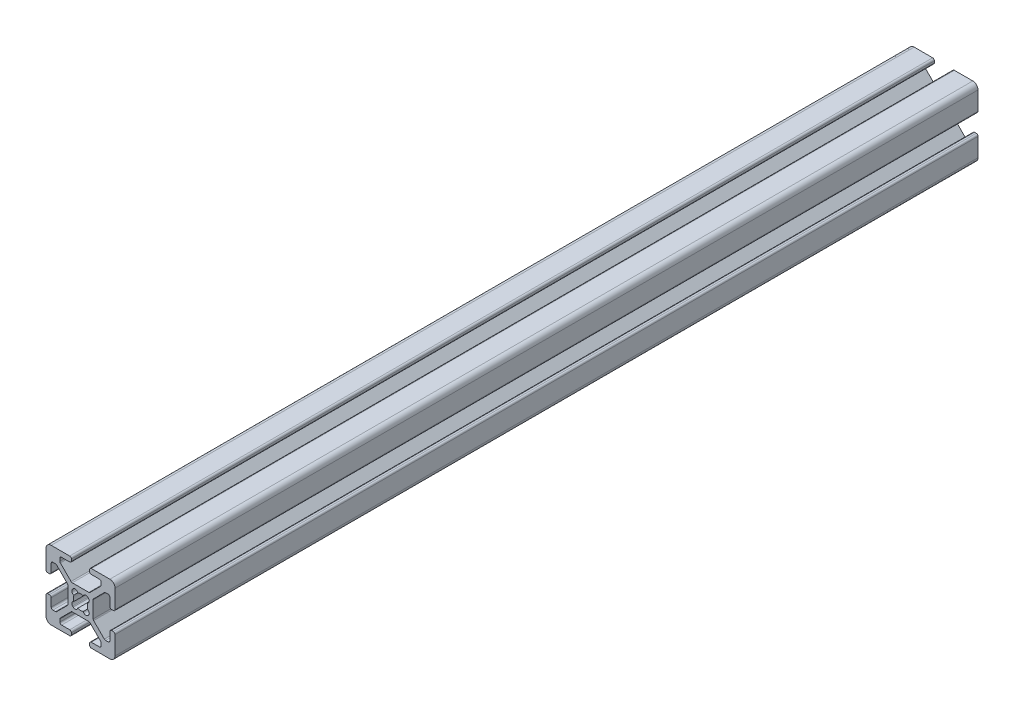
SolidWorks part; units mm, degrees
material "1060 Alloy"
ref_plane "Front Plane" through (0, 0, 0) normal (0, 0, 1) x (1, 0, 0)
ref_plane "Top Plane" through (0, 0, 0) normal (0, 1, 0) x (1, 0, 0)
ref_plane "Right Plane" through (0, 0, 0) normal (1, 0, 0) x (0, 0, -1)
sketch "Sketch2" plane through (0, 0, 0) normal (0, 0, 1) x (1, 0, 0)
  line L0 (-10, -3.138) -> (-10, -8.5)
  line L1 (-8.5, -10) -> (-3.138, -10)
  line L2 (-2.63, -9.492) -> (-2.63, -9.008)
  line L3 (-3.138, -8.5) -> (-5.487, -8.5)
  line L4 (-5.995, -7.992) -> (-5.995, -7.2662)
  line L5 (-5.8462, -6.907) -> (-2.743, -3.8038)
  line L6 (-2.3838, -3.655) -> (2.3841, -3.655)
  line L7 (2.7433, -3.8038) -> (5.8462, -6.9067)
  line L8 (5.995, -7.2659) -> (5.995, -7.992)
  line L9 (5.487, -8.5) -> (3.138, -8.5)
  line L10 (2.63, -9.008) -> (2.63, -9.492)
  line L11 (3.138, -10) -> (8.5, -10)
  line L12 (10, -8.5) -> (10, -3.138)
  line L13 (9.492, -2.63) -> (9.008, -2.63)
  line L14 (8.5, -3.138) -> (8.5, -5.487)
  line L15 (7.992, -5.995) -> (7.2662, -5.995)
  line L16 (6.907, -5.8462) -> (3.8038, -2.743)
  line L17 (3.655, -2.3838) -> (3.655, 2.3841)
  line L18 (3.8038, 2.7433) -> (6.9067, 5.8462)
  line L19 (7.2659, 5.995) -> (7.992, 5.995)
  line L20 (8.5, 5.487) -> (8.5, 3.138)
  line L21 (9.008, 2.63) -> (9.492, 2.63)
  line L22 (10, 3.138) -> (10, 8.5)
  line L23 (8.5, 10) -> (3.138, 10)
  line L24 (2.63, 9.492) -> (2.63, 9.008)
  line L25 (3.138, 8.5) -> (5.487, 8.5)
  line L26 (5.995, 7.992) -> (5.995, 7.2662)
  line L27 (5.8462, 6.907) -> (2.743, 3.8038)
  line L28 (2.3838, 3.655) -> (-2.3841, 3.655)
  line L29 (-2.7433, 3.8038) -> (-5.8462, 6.9067)
  line L30 (-5.995, 7.2659) -> (-5.995, 7.992)
  line L31 (-5.487, 8.5) -> (-3.138, 8.5)
  line L32 (-2.63, 9.008) -> (-2.63, 9.492)
  line L33 (-3.138, 10) -> (-8.5, 10)
  line L34 (-10, 8.5) -> (-10, 3.138)
  line L35 (-9.492, 2.63) -> (-9.008, 2.63)
  line L36 (-8.5, 3.138) -> (-8.5, 5.487)
  line L37 (-7.992, 5.995) -> (-7.2662, 5.995)
  line L38 (-6.907, 5.8462) -> (-3.8038, 2.743)
  line L39 (-3.655, 2.3838) -> (-3.655, -2.3841)
  line L40 (-3.8038, -2.7433) -> (-6.9067, -5.8462)
  line L41 (-7.2659, -5.995) -> (-7.992, -5.995)
  line L42 (-8.5, -5.487) -> (-8.5, -3.138)
  line L43 (-9.008, -2.63) -> (-9.492, -2.63)
  line L44 (-2.1245, 2.3045) -> (-2.3045, 2.1245)
  line L45 (2.3045, 2.1245) -> (2.1245, 2.3045)
  line L46 (2.1245, -2.3045) -> (2.3045, -2.1245)
  line L47 (-2.3045, -2.1245) -> (-2.1245, -2.3045)
  arc A0 (-10, -8.5) -> (-8.5, -10) centre (-8.5, -8.5) ccw
  arc A1 (-3.138, -10) -> (-2.63, -9.492) centre (-3.138, -9.492) ccw
  arc A2 (-2.63, -9.008) -> (-3.138, -8.5) centre (-3.138, -9.008) ccw
  arc A3 (-5.995, -7.992) -> (-5.487, -8.5) centre (-5.487, -7.992) ccw
  arc A4 (-5.8462, -6.907) -> (-5.995, -7.2662) centre (-5.487, -7.2662) ccw
  arc A5 (-2.3838, -3.655) -> (-2.743, -3.8038) centre (-2.3838, -4.163) ccw
  arc A6 (2.7433, -3.8038) -> (2.3841, -3.655) centre (2.3841, -4.163) ccw
  arc A7 (5.995, -7.2659) -> (5.8462, -6.9067) centre (5.487, -7.2659) ccw
  arc A8 (5.487, -8.5) -> (5.995, -7.992) centre (5.487, -7.992) ccw
  arc A9 (3.138, -8.5) -> (2.63, -9.008) centre (3.138, -9.008) ccw
  arc A10 (2.63, -9.492) -> (3.138, -10) centre (3.138, -9.492) ccw
  arc A11 (8.5, -10) -> (10, -8.5) centre (8.5, -8.5) ccw
  arc A12 (10, -3.138) -> (9.492, -2.63) centre (9.492, -3.138) ccw
  arc A13 (9.008, -2.63) -> (8.5, -3.138) centre (9.008, -3.138) ccw
  arc A14 (7.992, -5.995) -> (8.5, -5.487) centre (7.992, -5.487) ccw
  arc A15 (6.907, -5.8462) -> (7.2662, -5.995) centre (7.2662, -5.487) ccw
  arc A16 (3.655, -2.3838) -> (3.8038, -2.743) centre (4.163, -2.3838) ccw
  arc A17 (3.8038, 2.7433) -> (3.655, 2.3841) centre (4.163, 2.3841) ccw
  arc A18 (7.2659, 5.995) -> (6.9067, 5.8462) centre (7.2659, 5.487) ccw
  arc A19 (8.5, 5.487) -> (7.992, 5.995) centre (7.992, 5.487) ccw
  arc A20 (8.5, 3.138) -> (9.008, 2.63) centre (9.008, 3.138) ccw
  arc A21 (9.492, 2.63) -> (10, 3.138) centre (9.492, 3.138) ccw
  arc A22 (10, 8.5) -> (8.5, 10) centre (8.5, 8.5) ccw
  arc A23 (3.138, 10) -> (2.63, 9.492) centre (3.138, 9.492) ccw
  arc A24 (2.63, 9.008) -> (3.138, 8.5) centre (3.138, 9.008) ccw
  arc A25 (5.995, 7.992) -> (5.487, 8.5) centre (5.487, 7.992) ccw
  arc A26 (5.8462, 6.907) -> (5.995, 7.2662) centre (5.487, 7.2662) ccw
  arc A27 (2.3838, 3.655) -> (2.743, 3.8038) centre (2.3838, 4.163) ccw
  arc A28 (-2.7433, 3.8038) -> (-2.3841, 3.655) centre (-2.3841, 4.163) ccw
  arc A29 (-5.995, 7.2659) -> (-5.8462, 6.9067) centre (-5.487, 7.2659) ccw
  arc A30 (-5.487, 8.5) -> (-5.995, 7.992) centre (-5.487, 7.992) ccw
  arc A31 (-3.138, 8.5) -> (-2.63, 9.008) centre (-3.138, 9.008) ccw
  arc A32 (-2.63, 9.492) -> (-3.138, 10) centre (-3.138, 9.492) ccw
  arc A33 (-8.5, 10) -> (-10, 8.5) centre (-8.5, 8.5) ccw
  arc A34 (-10, 3.138) -> (-9.492, 2.63) centre (-9.492, 3.138) ccw
  arc A35 (-9.008, 2.63) -> (-8.5, 3.138) centre (-9.008, 3.138) ccw
  arc A36 (-7.992, 5.995) -> (-8.5, 5.487) centre (-7.992, 5.487) ccw
  arc A37 (-6.907, 5.8462) -> (-7.2662, 5.995) centre (-7.2662, 5.487) ccw
  arc A38 (-3.655, 2.3838) -> (-3.8038, 2.743) centre (-4.163, 2.3838) ccw
  arc A39 (-3.8038, -2.7433) -> (-3.655, -2.3841) centre (-4.163, -2.3841) ccw
  arc A40 (-7.2659, -5.995) -> (-6.9067, -5.8462) centre (-7.2659, -5.487) ccw
  arc A41 (-8.5, -5.487) -> (-7.992, -5.995) centre (-7.992, -5.487) ccw
  arc A42 (-8.5, -3.138) -> (-9.008, -2.63) centre (-9.008, -3.138) ccw
  arc A43 (-9.492, -2.63) -> (-10, -3.138) centre (-9.492, -3.138) ccw
  arc A44 (-1.9358, 0.8037) -> (-1.9358, -0.8037) centre (0, 0) ccw
  arc A45 (-2.3045, 2.1245) -> (-1.9358, 0.8037) centre (-1.748, 1.568) ccw
  arc A46 (-0.8037, 1.9358) -> (-2.1245, 2.3045) centre (-1.568, 1.748) ccw
  arc A47 (0.8037, 1.9358) -> (-0.8037, 1.9358) centre (0, 0) ccw
  arc A48 (2.1245, 2.3045) -> (0.8037, 1.9358) centre (1.568, 1.748) ccw
  arc A49 (1.9358, 0.8037) -> (2.3045, 2.1245) centre (1.748, 1.568) ccw
  arc A50 (1.9358, -0.8037) -> (1.9358, 0.8037) centre (0, 0) ccw
  arc A51 (2.3045, -2.1245) -> (1.9358, -0.8037) centre (1.748, -1.568) ccw
  arc A52 (0.8037, -1.9358) -> (2.1245, -2.3045) centre (1.568, -1.748) ccw
  arc A53 (-0.8037, -1.9358) -> (0.8037, -1.9358) centre (0, 0) ccw
  arc A54 (-2.1245, -2.3045) -> (-0.8037, -1.9358) centre (-1.568, -1.748) ccw
  arc A55 (-1.9358, -0.8037) -> (-2.3045, -2.1245) centre (-1.748, -1.568) ccw
extrude "Boss-Extrude1" add sketch "Sketch2" against normal blind 250
